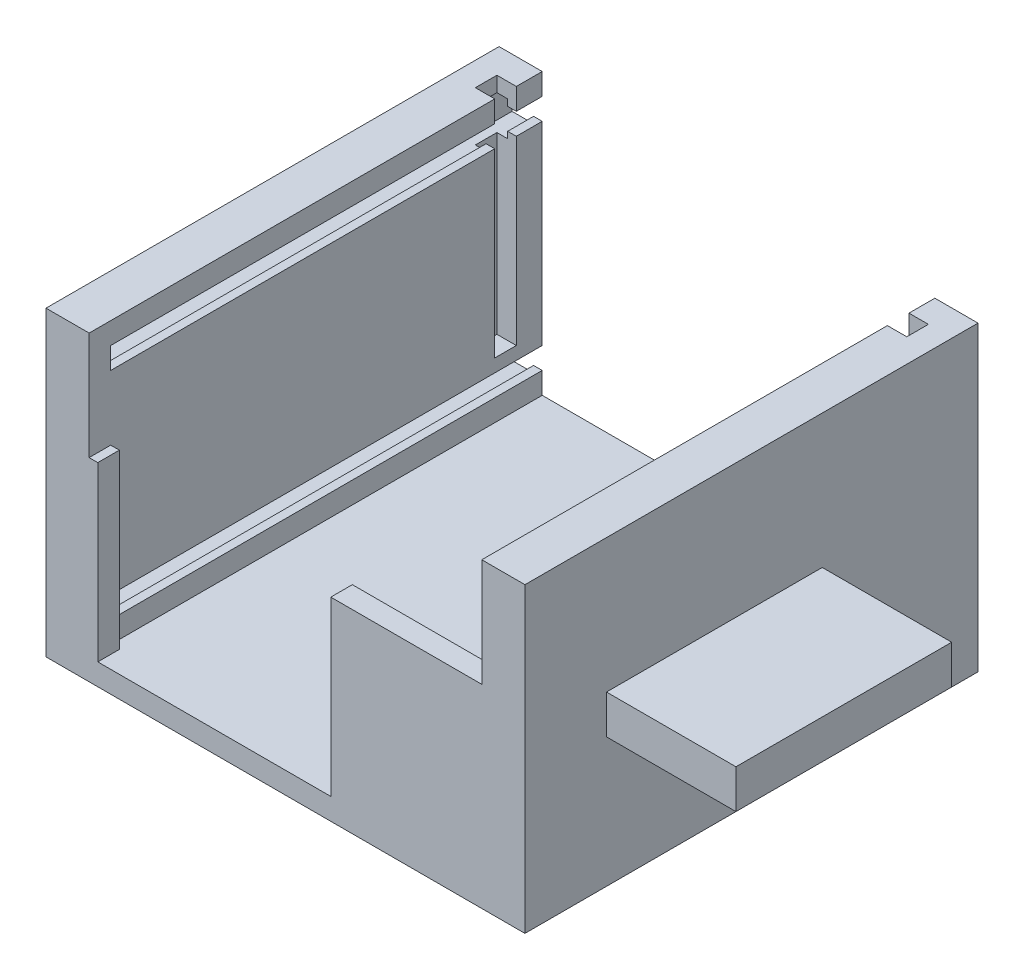
SolidWorks part; units mm, degrees
ref_plane "Front Plane" through (0, 0, 0) normal (0, 0, 1) x (1, 0, 0)
ref_plane "Top Plane" through (0, 0, 0) normal (0, 1, 0) x (1, 0, 0)
ref_plane "Right Plane" through (0, 0, 0) normal (1, 0, 0) x (0, 0, -1)
sketch "Sketch1" plane through (0, 0, 0) normal (0, 0, 1) x (1, 0, 0)
  line L0 (-45.5, 30) -> (-45.5, 35)
  line L1 (-45.5, -30) -> (45.5, -30)
  line L2 (-45.5, -30) -> (-45.5, 30)
  line L4 (45.5, -30) -> (45.5, 30)
  line L5 (-45.5, -30) -> (45.5, 30) construction
  line L6 (-45.5, 30) -> (45.5, -30) construction
  line L7 (-55.5, -35) -> (55.5, -35)
  line L8 (-55.5, -35) -> (-55.5, 35)
  line L9 (-55.5, 35) -> (-45.5, 35)
  line L10 (55.5, -35) -> (55.5, 35)
  line L11 (-55.5, -35) -> (55.5, 35) construction
  line L12 (-55.5, 35) -> (55.5, -35) construction
  line L13 (45.5, 30) -> (45.5, 35)
  line L14 (45.5, 35) -> (55.5, 35)
  point P0 (0, 0)
  point P5 (0, 0)
  dimension "D1" = 91
  dimension "D2" = 111
  dimension "D3" = 70
  dimension "D4" = 60
extrude "Boss-Extrude1" add sketch "Sketch1" along normal mid plane 100
sketch "Sketch2" plane through (0, 0, 50) normal (0, 0, 1) x (1, 0, 0)
  line L0 (-66.209, -22.5) -> (73.9679, -22.5) construction
  line L1 (-68.4074, 27.5) -> (72.5454, 27.5) construction
  line L2 (45.5, -30) -> (-45.5, -30) construction
  line L3 (0, 39.2469) -> (0, -38.859) construction
  line L4 (-45.5, -30) -> (-45.5, 35) construction
  line L5 (-47.5, 25) -> (-45.5, 25)
  line L7 (-47.5, 30) -> (-45.5, 30)
  line L8 (-45.5, 25) -> (-45.5, 30)
  line L9 (-47.5, 25) -> (-45.5, 30) construction
  line L10 (-47.5, 30) -> (-45.5, 25) construction
  line L11 (-68.4074, 2.5) -> (77.3475, 2.5) construction
  line L12 (-52.5, 23.5) -> (-47.5, 23.5)
  line L13 (-52.5, 23.5) -> (-52.5, 31.5)
  line L14 (-52.5, 31.5) -> (-47.5, 31.5)
  line L15 (-47.5, 23.5) -> (-47.5, 25)
  line L16 (-52.5, 23.5) -> (-47.5, 31.5) construction
  line L17 (-52.5, 31.5) -> (-47.5, 23.5) construction
  line L18 (52.5, 31.5) -> (47.5, 23.5) construction
  line L19 (52.5, 23.5) -> (47.5, 31.5) construction
  line L20 (47.5, 30) -> (45.5, 25) construction
  line L21 (47.5, 25) -> (45.5, 30) construction
  line L22 (68.4074, 27.5) -> (-72.5454, 27.5) construction
  line L23 (47.5, 23.5) -> (47.5, 25)
  line L24 (52.5, 31.5) -> (47.5, 31.5)
  line L25 (52.5, 23.5) -> (52.5, 31.5)
  line L26 (52.5, 23.5) -> (47.5, 23.5)
  line L27 (45.5, 25) -> (45.5, 30)
  line L28 (47.5, 30) -> (45.5, 30)
  line L30 (47.5, 25) -> (45.5, 25)
  line L31 (47.5, -20) -> (45.5, -25) construction
  line L32 (47.5, -25) -> (45.5, -20) construction
  line L33 (52.5, -18.5) -> (47.5, -26.5) construction
  line L34 (52.5, -26.5) -> (47.5, -18.5) construction
  line L35 (47.5, -20) -> (45.5, -20)
  line L37 (47.5, -25) -> (45.5, -25)
  line L38 (45.5, -20) -> (45.5, -25)
  line L39 (52.5, -18.5) -> (47.5, -18.5)
  line L40 (52.5, -18.5) -> (52.5, -26.5)
  line L41 (52.5, -26.5) -> (47.5, -26.5)
  line L42 (47.5, -18.5) -> (47.5, -20)
  line L43 (68.4074, -22.5) -> (-72.5454, -22.5) construction
  line L44 (-52.5, -26.5) -> (-47.5, -18.5) construction
  line L45 (-52.5, -18.5) -> (-47.5, -26.5) construction
  line L46 (-47.5, -25) -> (-45.5, -20) construction
  line L47 (-47.5, -20) -> (-45.5, -25) construction
  line L48 (-68.4074, -22.5) -> (72.5454, -22.5) construction
  line L49 (-47.5, -18.5) -> (-47.5, -20)
  line L50 (-52.5, -26.5) -> (-47.5, -26.5)
  line L51 (-52.5, -18.5) -> (-52.5, -26.5)
  line L52 (-52.5, -18.5) -> (-47.5, -18.5)
  line L53 (-45.5, -20) -> (-45.5, -25)
  line L54 (-47.5, -25) -> (-45.5, -25)
  line L56 (-47.5, -20) -> (-45.5, -20)
  line L57 (-47.5, 30) -> (-47.5, 31.5)
  line L58 (47.5, 30) -> (47.5, 31.5)
  line L59 (47.5, -25) -> (47.5, -26.5)
  line L60 (-47.5, -25) -> (-47.5, -26.5)
  point P9 (-46.5, 27.5)
  point P16 (-50, 27.5)
  point P33 (50, 27.5)
  point P34 (46.5, 27.5)
  point P42 (46.5, -22.5)
  point P43 (50, -22.5)
  point P56 (-50, -22.5)
  point P57 (-46.5, -22.5)
  dimension "D1" = 50
  dimension "D2" = 7.5
  dimension "D3" = 2
  dimension "D4" = 5
  dimension "D5" = 8
  dimension "D6" = 5
  dimension "D7" = 25
extrude "Cut-Extrude3" cut sketch "Sketch2" against normal through all contours L5 L8 L7 L57 L14 L13 L12 L15 | L23 L30 L27 L28 L58 L24 L25 L26 | L39 L42 L35 L38 L37 L59 L41 L40 | L60 L50 L51 L52 L49 L56 L53 L54
sketch "Sketch3" plane through (0, 0, 50) normal (0, 0, 1) x (1, 0, 0)
  line L5 (-55.5, 35) -> (-55.5, -35) construction
  line L6 (-55.5, 35) -> (-45.5, 35)
  line L7 (-55.5, 35) -> (-55.5, -35)
  line L8 (-55.5, -35) -> (55.5, -35)
  line L9 (55.5, 35) -> (55.5, -35)
  line L10 (-45.5, 30) -> (-45.5, 35) construction
  line L12 (-45.5, 35) -> (-45.5, -30)
  line L13 (-45.5, -30) -> (45.5, -30)
  line L14 (45.5, 35) -> (45.5, -30)
  line L15 (45.5, -30) -> (-45.5, -30) construction
  line L16 (45.5, 35) -> (55.5, 35)
  line L17 (-45.5, 10) -> (-43.5, 10)
  line L18 (-45.5, 10) -> (-45.5, -30)
  line L19 (-45.5, -30) -> (-43.5, -30)
  line L20 (-43.5, 10) -> (-43.5, -30)
  line L25 (10.5, 10) -> (45.5, 10)
  line L26 (10.5, 10) -> (10.5, -30)
  line L27 (10.5, -30) -> (45.5, -30)
  line L28 (45.5, 10) -> (45.5, -30)
  point P23 (0, -30)
  line M20 (-45.5, -30) -> (-45.5, -25)
  line M21 (-45.5, -25) -> (-47.5, -25)
  line M22 (-47.5, -25) -> (-47.5, -26.5)
  line M23 (-47.5, -26.5) -> (-52.5, -26.5)
  line M24 (-52.5, -26.5) -> (-52.5, -18.5)
  line M25 (-52.5, -18.5) -> (-47.5, -18.5)
  line M26 (-47.5, -18.5) -> (-47.5, -20)
  line M27 (-47.5, -20) -> (-45.5, -20)
  line M28 (-45.5, -20) -> (-45.5, 25)
  line M29 (-45.5, 25) -> (-47.5, 25)
  line M30 (-47.5, 25) -> (-47.5, 23.5)
  line M31 (-47.5, 23.5) -> (-52.5, 23.5)
  line M32 (-52.5, 23.5) -> (-52.5, 31.5)
  line M33 (-52.5, 31.5) -> (-47.5, 31.5)
  line M34 (-47.5, 31.5) -> (-47.5, 30)
  line M35 (-47.5, 30) -> (-45.5, 30)
  line M36 (-45.5, 30) -> (-45.5, 35)
  line M37 (-45.5, 35) -> (-55.5, 35)
  line M38 (-55.5, 35) -> (-55.5, -35)
  line M39 (-55.5, -35) -> (55.5, -35)
  line M40 (55.5, -35) -> (55.5, 35)
  line M41 (55.5, 35) -> (45.5, 35)
  line M42 (45.5, 35) -> (45.5, 30)
  line M43 (45.5, 30) -> (47.5, 30)
  line M44 (47.5, 30) -> (47.5, 31.5)
  line M45 (47.5, 31.5) -> (52.5, 31.5)
  line M46 (52.5, 31.5) -> (52.5, 23.5)
  line M47 (52.5, 23.5) -> (47.5, 23.5)
  line M48 (47.5, 23.5) -> (47.5, 25)
  line M49 (47.5, 25) -> (45.5, 25)
  line M50 (45.5, 25) -> (45.5, -20)
  line M51 (45.5, -20) -> (47.5, -20)
  line M52 (47.5, -20) -> (47.5, -18.5)
  line M53 (47.5, -18.5) -> (52.5, -18.5)
  line M54 (52.5, -18.5) -> (52.5, -26.5)
  line M55 (52.5, -26.5) -> (47.5, -26.5)
  line M56 (47.5, -26.5) -> (47.5, -25)
  line M57 (47.5, -25) -> (45.5, -25)
  line M58 (45.5, -25) -> (45.5, -30)
  line M59 (45.5, -30) -> (-45.5, -30)
  dimension "D1" = 10
  dimension "D2" = 2
  dimension "D3" = 35
  dimension "D4" = 40
  dimension "D5" = 40
  dimension "D6" = 70
extrude "Boss-Extrude2" add sketch "Sketch3" along normal blind 5 contours L25 L26 L14 M59 M58 | L13 L12 L14 M59 M20 M21 M22 M23 M24 M25 M26 M27 M28 M29 M30 M31 M32 M33 M34 M35 M36 M37 M38 M39 M40 M41 M42 M43 M44 M45 M46 M47 M48 M49 M50 M51 M52 M53 M54 M55 M56 M57 M58 | L20 L17 L12 L13 M28 M20 | L14 M51 M57 M56 M55 M54 M53 M52 | L14 M43 M49 M48 M47 M46 M45 M44 | L12 M27 M26 M25 M24 M23 M22 M21 | L12 M35 M34 M33 M32 M31 M30 M29
sketch "Sketch4" plane through (0, 0, 0) normal (0, 1, 0) x (1, 0, 0)
  line L0 (45.5, 50) -> (-45.5, 50) construction
  line L1 (-50, 39) -> (50, 39)
  line L2 (-50, 39) -> (-50, 44)
  line L3 (-50, 44) -> (50, 44)
  line L4 (50, 39) -> (50, 44)
  line L5 (-50, 39) -> (50, 44) construction
  line L6 (-50, 44) -> (50, 39) construction
  point P0 (0, 41.5)
  dimension "D1" = 5
  dimension "D2" = 100
  dimension "D3" = 6
extrude "Cut-Extrude4" cut sketch "Sketch4" against normal blind 52 from surface at 35 starting at face at (-50.5, 35, 2.5)
sketch "Sketch5" plane through (55.5, 0, 0) normal (1, 0, 0) x (0, 0, -1)
  line L0 (-36.0974, -5) -> (-36.0974, 4)
  line L1 (-36.0974, 4) -> (13.9026, 4)
  line L2 (13.9026, 4) -> (13.9026, -5)
  line L3 (13.9026, -5) -> (-36.0974, -5)
  dimension "D1" = 9
  dimension "D2" = 50
extrude "Boss-Extrude3" add sketch "Sketch5" along normal blind 30
